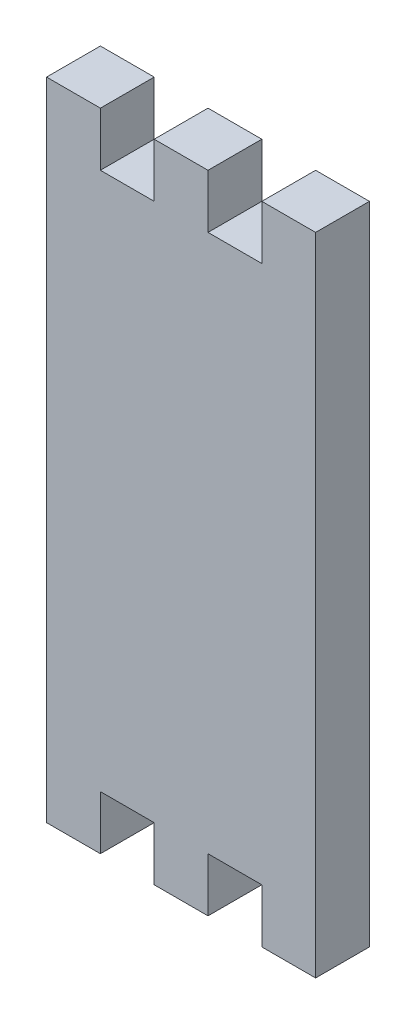
SolidWorks part; units mm, degrees
ref_plane "Front Plane" through (0, 0, 0) normal (0, 0, 1) x (1, 0, 0)
ref_plane "Top Plane" through (0, 0, 0) normal (0, 1, 0) x (1, 0, 0)
ref_plane "Right Plane" through (0, 0, 0) normal (1, 0, 0) x (0, 0, -1)
sketch "Sketch1" plane through (0, 0, 0) normal (0, 0, 1) x (1, 0, 0)
  line L0 (9.9165, 18.0898) -> (9.9165, -17.9102) construction
  line L1 (2.4165, 18.0898) -> (5.4165, 18.0898)
  line L2 (2.4165, 18.0898) -> (2.4165, -17.9102)
  line L3 (2.4165, -17.9102) -> (5.4165, -17.9102)
  line L4 (17.4165, 18.0898) -> (17.4165, -17.9102)
  line L5 (5.4165, -14.9102) -> (8.4165, -14.9102)
  line L6 (5.4165, -14.9102) -> (5.4165, -17.9102)
  line L8 (8.4165, -14.9102) -> (8.4165, -17.9102)
  line L10 (11.4165, -14.9102) -> (11.4165, -17.9102)
  line L11 (14.4165, -14.9102) -> (11.4165, -14.9102)
  line L12 (14.4165, -14.9102) -> (14.4165, -17.9102)
  line L13 (2.4165, 0.0898) -> (17.4165, 0.0898) construction
  line L14 (14.4165, 15.0898) -> (14.4165, 18.0898)
  line L15 (14.4165, 15.0898) -> (11.4165, 15.0898)
  line L16 (11.4165, 15.0898) -> (11.4165, 18.0898)
  line L19 (8.4165, 15.0898) -> (8.4165, 18.0898)
  line L20 (5.4165, 15.0898) -> (8.4165, 15.0898)
  line L21 (5.4165, 15.0898) -> (5.4165, 18.0898)
  line L22 (8.4165, 18.0898) -> (11.4165, 18.0898)
  line L23 (14.4165, 18.0898) -> (17.4165, 18.0898)
  line L24 (8.4165, -17.9102) -> (11.4165, -17.9102)
  line L25 (14.4165, -17.9102) -> (17.4165, -17.9102)
  dimension "D1" = 36
  dimension "D2" = 15
  dimension "D3" = 3
  dimension "D4" = 3
  dimension "D6" = 3
extrude "Boss-Extrude1" add sketch "Sketch1" along normal blind 3
